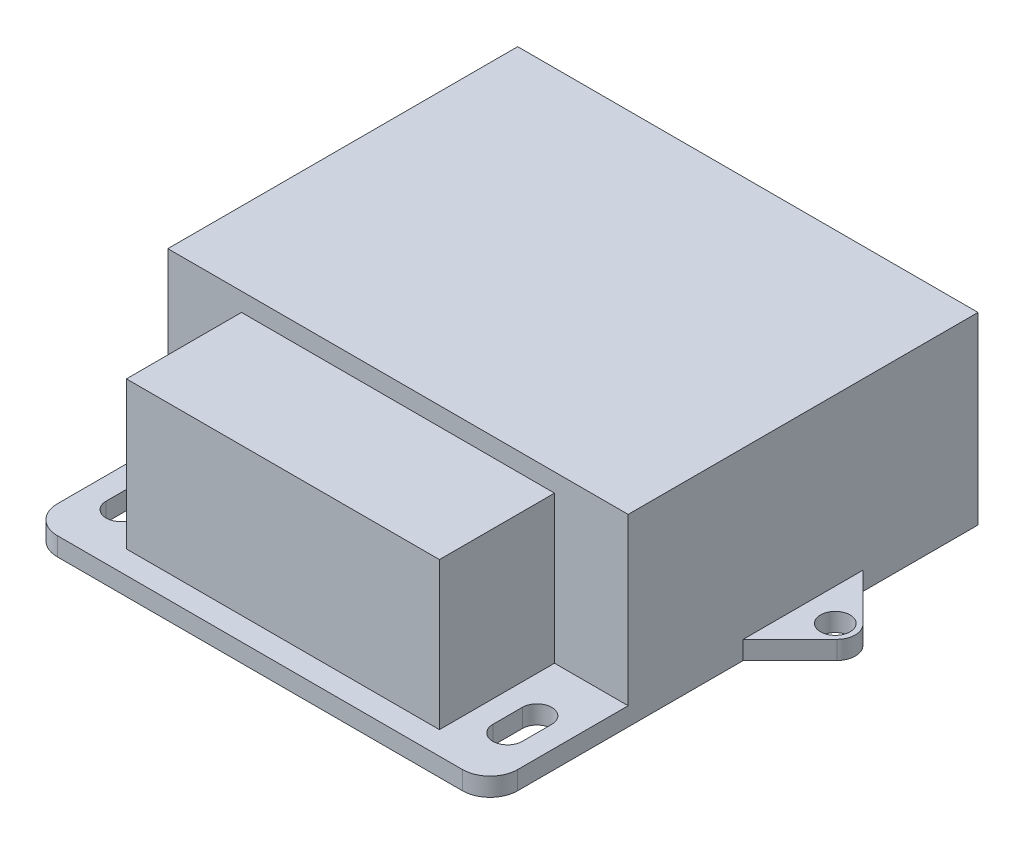
SolidWorks part; units mm, degrees
ref_plane "Płaszczyzna przednia" through (0, 0, 0) normal (0, 0, 1) x (1, 0, 0)
ref_plane "Płaszczyzna górna" through (0, 0, 0) normal (0, 1, 0) x (1, 0, 0)
ref_plane "Płaszczyzna prawa" through (0, 0, 0) normal (1, 0, 0) x (0, 0, -1)
sketch "Szkic2" plane through (0, 0, 0) normal (0, 1, 0) x (1, 0, 0)
  line L0 (0, -26.5) -> (0, -19) construction
  line L1 (-25, 26.5) -> (25, 26.5)
  line L2 (-25, 26.5) -> (-25, -26.5)
  line L3 (-25, -26.5) -> (25, -26.5)
  line L4 (25, 26.5) -> (25, -26.5)
  line L5 (-25, 26.5) -> (25, -26.5) construction
  line L6 (-25, -26.5) -> (25, 26.5) construction
  line L7 (-21, -19) -> (21, -19) construction
  line L8 (21, -17.4) -> (21, -20.6) construction
  line L9 (22.6, -17.4) -> (22.6, -20.6)
  line L10 (19.4, -17.4) -> (19.4, -20.6)
  line L11 (-21, -17.4) -> (-21, -20.6) construction
  line L12 (-22.6, -17.4) -> (-22.6, -20.6)
  line L13 (-19.4, -17.4) -> (-19.4, -20.6)
  arc A0 (22.6, -17.4) -> (19.4, -17.4) centre (21, -17.4) ccw
  arc A1 (19.4, -20.6) -> (22.6, -20.6) centre (21, -20.6) ccw
  arc A2 (-22.6, -17.4) -> (-19.4, -17.4) centre (-21, -17.4) cw
  arc A3 (-19.4, -20.6) -> (-22.6, -20.6) centre (-21, -20.6) cw
  point P0 (0, 0)
  point P11 (0, -19)
  point P13 (21, -19)
  point P20 (-21, -19)
  dimension "D5" = 3.2
  dimension "D1" = 50
  dimension "D2" = 53
  dimension "D3" = 42
  dimension "D4" = 7.5
  dimension "D6" = 3.2
extrude "Dodanie-wyciągnięcie1" add sketch "Szkic2" along normal blind 2
fillet "Zaokrąglenie1" radius 3 2 edges at (-25, 1, 26.5) (25, 1, 26.5)
sketch "Szkic3" plane through (0, 2, 0) normal (0, 1, 0) x (1, 0, 0)
  line L0 (-25, 26.5) -> (-25, -23.5) construction
  line L1 (25, 26.5) -> (-25, 26.5)
  line L2 (25, 26.5) -> (25, -11.5)
  line L3 (25, -11.5) -> (-25, -11.5)
  line L4 (-25, 26.5) -> (-25, -11.5)
  line L5 (25, 26.5) -> (-25, -11.5) construction
  line L6 (25, -11.5) -> (-25, 26.5) construction
  point P4 (0, 7.5)
  dimension "D1" = 38
extrude "Dodanie-wyciągnięcie2" add sketch "Szkic3" along normal blind 18
sketch "Szkic4" plane through (0, 2, 0) normal (0, 1, 0) x (1, 0, 0)
  line L0 (-25, -11.5) -> (25, -11.5) construction
  line L1 (17, -11.5) -> (-17, -11.5)
  line L2 (17, -11.5) -> (17, -24)
  line L3 (17, -24) -> (-17, -24)
  line L4 (-17, -11.5) -> (-17, -24)
  line L5 (17, -11.5) -> (-17, -24) construction
  line L6 (17, -24) -> (-17, -11.5) construction
  line L7 (25, -23.5) -> (25, -11.5) construction
  line L8 (-25, -11.5) -> (-25, -23.5) construction
  line L9 (-22, -26.5) -> (22, -26.5) construction
  point P4 (0, -17.75)
  dimension "D1" = 8
  dimension "D2" = 8
  dimension "D3" = 2.5
extrude "Dodanie-wyciągnięcie3" add sketch "Szkic4" along normal blind 16
sketch "Szkic5" plane through (0, 2, 0) normal (0, 1, 0) x (1, 0, 0)
  line L0 (-25, 26.5) -> (-25, 7.5) construction
  line L1 (-25, 26.5) -> (-25, -11.5) construction
  line L2 (-25, 7.5) -> (-28.5, 7.5) construction
  line L3 (-28.5, 7.5) -> (-31.5, 7.5) construction
  line L4 (-31.5, 7.5) -> (-25, 14)
  line L5 (-31.5, 7.5) -> (-25, 1)
  line L6 (-25, 1) -> (-25, 14)
  circle A0 centre (-28.5, 7.5) radius 1.6
  dimension "D3" = 3.2
  dimension "D1" = 3.5
  dimension "D2" = 3
extrude "Dodanie-wyciągnięcie4" add sketch "Szkic5" against normal blind 2
mirror "Lustro1" about plane through (0, 0, 0) normal (1, 0, 0) of "Dodanie-wyciągnięcie4"
fillet "Zaokrąglenie2" radius 2 2 edges at (31.5, 1, -7.5) (-31.5, 1, -7.5)
